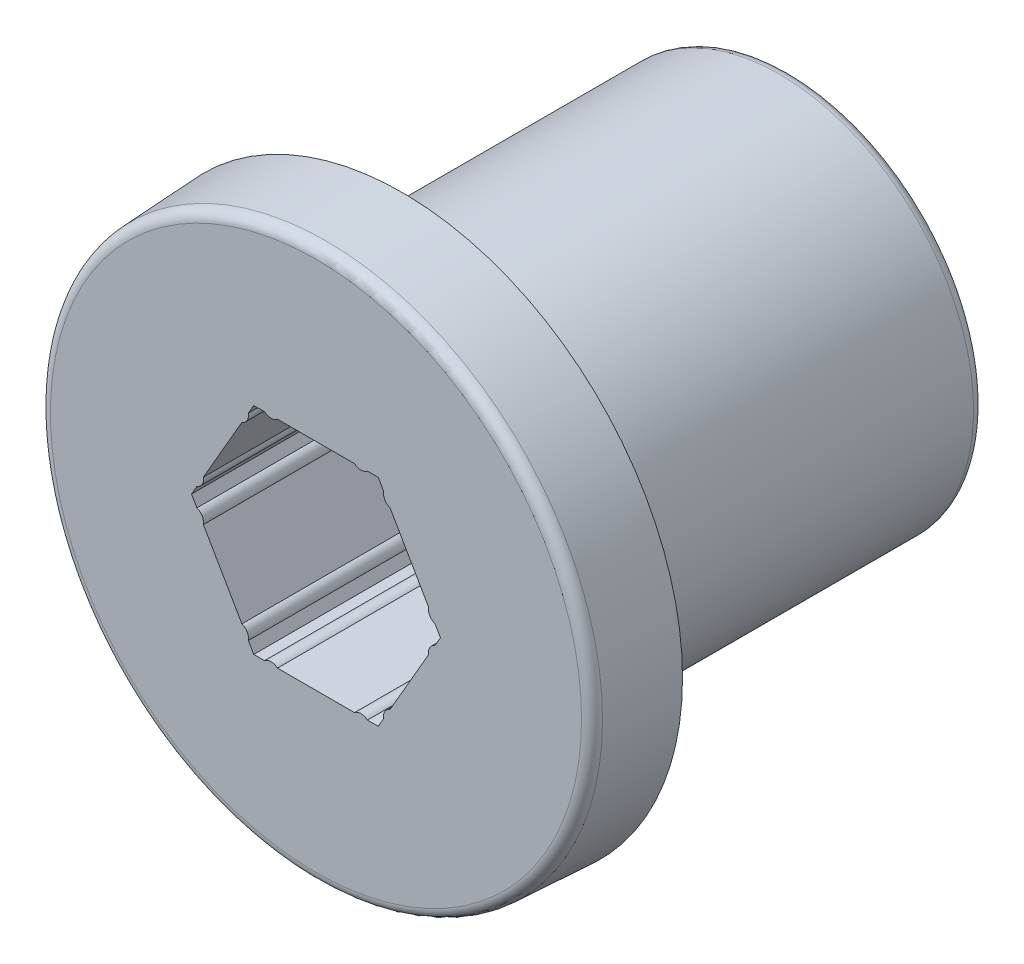
SolidWorks part; units mm, degrees
material "Rubber"
ref_plane "Front Plane" through (0, 0, 0) normal (0, 0, 1) x (1, 0, 0)
ref_plane "Top Plane" through (0, 0, 0) normal (0, 1, 0) x (1, 0, 0)
ref_plane "Right Plane" through (0, 0, 0) normal (1, 0, 0) x (0, 0, -1)
sketch "Sketch1" plane through (0, 0, 0) normal (0, 1, 0) x (1, 0, 0)
  line L0 (6.5, 0) -> (0, 0)
  line L1 (0, 0) -> (0, -2)
  line L2 (0, -2) -> (6.3952, -2)
  line L3 (6.3952, -2) -> (6.5, 0)
  line L4 (0, 0) -> (0, -2) construction
revolve "Revolve1" add sketch "Sketch1" angle 360 about L4
sketch "Sketch2" plane through (0, 0, 0) normal (0, 0, -1) x (-1, 0, 0)
  circle A0 centre (0, 0) radius 4.5
extrude "Boss-Extrude1" add sketch "Sketch2" along normal blind 9
sketch "Sketch3" plane through (0, 0, -9) normal (0, 0, -1) x (-1, 0, 0)
  line L0 (1.1934, -2.5) -> (1.4434, -2.5)
  line L1 (1.4434, -2.5) -> (1.5684, -2.2835)
  line L2 (1.7184, -2.0237) -> (2.6118, -0.4763)
  line L3 (2.7618, -0.2165) -> (2.8868, 0)
  line L4 (2.8868, 0) -> (2.7618, 0.2165)
  line L5 (2.6118, 0.4763) -> (1.7184, 2.0237)
  line L6 (1.5684, 2.2835) -> (1.4434, 2.5)
  line L7 (1.4434, 2.5) -> (1.1934, 2.5)
  line L8 (0.8934, 2.5) -> (-0.8934, 2.5)
  line L9 (-1.1934, 2.5) -> (-1.4434, 2.5)
  line L10 (-1.4434, 2.5) -> (-1.5684, 2.2835)
  line L11 (-1.7184, 2.0237) -> (-2.6118, 0.4763)
  line L12 (-2.7618, 0.2165) -> (-2.8868, 0)
  line L13 (-2.8868, 0) -> (-2.7618, -0.2165)
  line L14 (-2.6118, -0.4763) -> (-1.7184, -2.0237)
  line L15 (-1.5684, -2.2835) -> (-1.4434, -2.5)
  line L16 (-1.4434, -2.5) -> (-1.1934, -2.5)
  line L17 (-0.8934, -2.5) -> (0.8934, -2.5)
  arc A0 (0.8934, -2.5) -> (1.1934, -2.5) centre (1.0434, -2.677) cw
  arc A1 (1.5684, -2.2835) -> (1.7184, -2.0237) centre (1.7967, -2.2421) cw
  arc A2 (2.6118, -0.4763) -> (2.7618, -0.2165) centre (2.8401, -0.4349) cw
  arc A3 (2.7618, 0.2165) -> (2.6118, 0.4763) centre (2.8401, 0.4349) cw
  arc A4 (1.7184, 2.0237) -> (1.5684, 2.2835) centre (1.7967, 2.2421) cw
  arc A5 (1.1934, 2.5) -> (0.8934, 2.5) centre (1.0434, 2.677) cw
  arc A6 (-0.8934, 2.5) -> (-1.1934, 2.5) centre (-1.0434, 2.677) cw
  arc A7 (-1.5684, 2.2835) -> (-1.7184, 2.0237) centre (-1.7967, 2.2421) cw
  arc A8 (-2.6118, 0.4763) -> (-2.7618, 0.2165) centre (-2.8401, 0.4349) cw
  arc A9 (-2.7618, -0.2165) -> (-2.6118, -0.4763) centre (-2.8401, -0.4349) cw
  arc A10 (-1.7184, -2.0237) -> (-1.5684, -2.2835) centre (-1.7967, -2.2421) cw
  arc A11 (-1.1934, -2.5) -> (-0.8934, -2.5) centre (-1.0434, -2.677) cw
extrude "Cut-Extrude1" cut sketch "Sketch3" against normal through all
fillet "Fillet1" radius 0.25 2 edges at (0, 4.5, -9) (6.3952, 0, 2)
